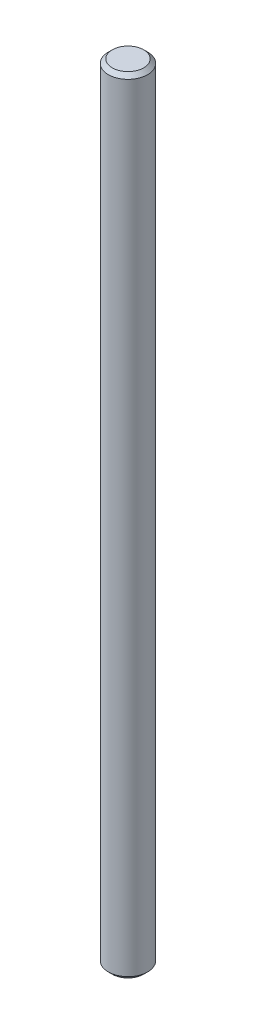
SolidWorks part; units mm, degrees
ref_plane "Front Plane" through (0, 0, 0) normal (0, 0, 1) x (1, 0, 0)
ref_plane "Top Plane" through (0, 0, 0) normal (0, 1, 0) x (1, 0, 0)
ref_plane "Right Plane" through (0, 0, 0) normal (1, 0, 0) x (0, 0, -1)
sketch "Sketch1" plane through (0, 0, 0) normal (0, 1, 0) x (1, 0, 0)
  circle A0 centre (0, 0) radius 5
  dimension "D1" = 10
extrude "Boss-Extrude1" add sketch "Sketch1" along normal blind 200
chamfer "Chamfer1" distance 1 angle 45 2 edges at (0, 0, 5) (0, 200, 5)
